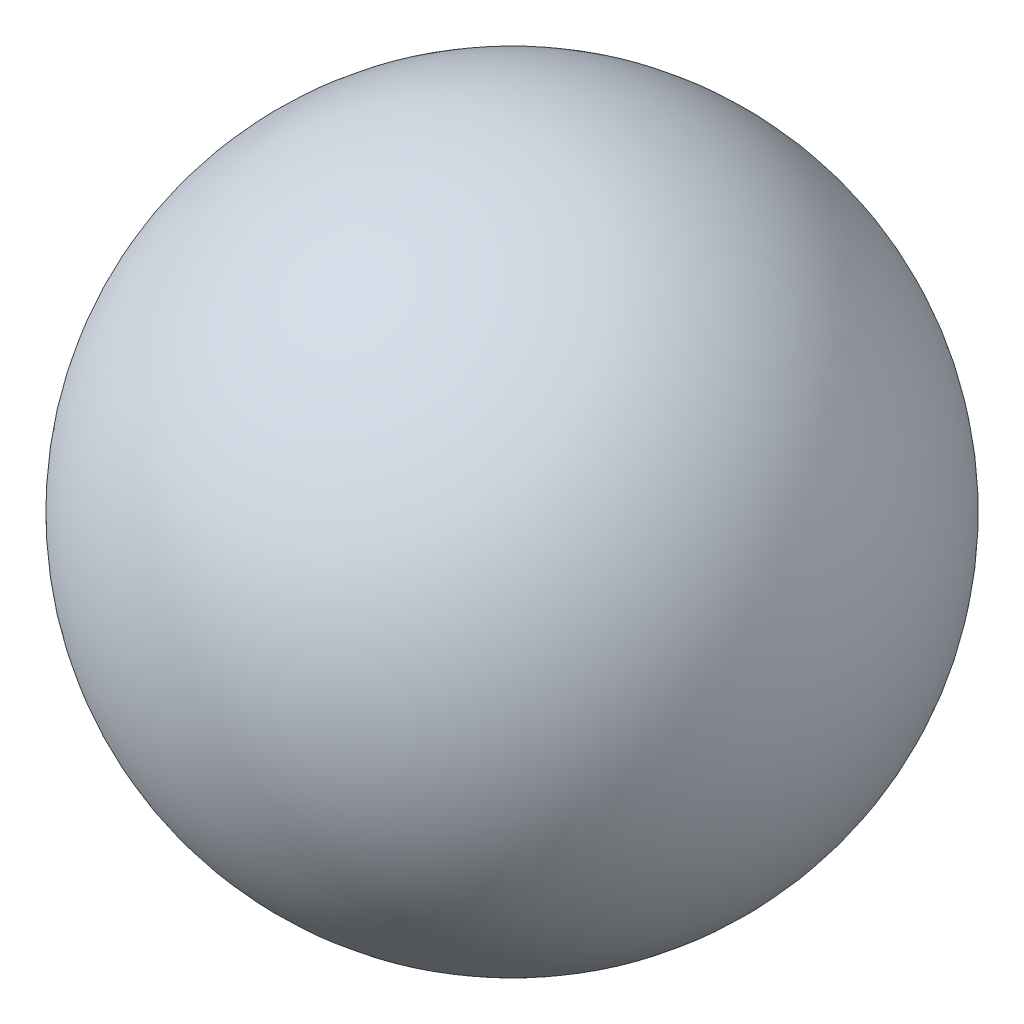
SolidWorks part; units mm, degrees
ref_plane "Front Plane" through (0, 0, 0) normal (0, 0, 1) x (1, 0, 0)
ref_plane "Top Plane" through (0, 0, 0) normal (0, 1, 0) x (1, 0, 0)
ref_plane "Right Plane" through (0, 0, 0) normal (1, 0, 0) x (0, 0, -1)
sketch "Sketch1" plane through (0, 0, 0) normal (0, 0, 1) x (1, 0, 0)
  line L1 (-50.5537, 931.9169) -> (50.5537, 931.9169) construction
  line L2 (0, 951.4169) -> (0, 943.4169)
  arc A0 (0, 943.4169) -> (0, 951.4169) centre (0, 947.4169) ccw
  point P4 (0, 931.9169)
  dimension "D1" = 8
  dimension "D2" = 31
revolve "Revolve1" add sketch "Sketch1" angle 360 about L2
equation "\"d_ext_rouleau\"= 90"
equation "\"epaisseur_rouleau\"=80"
equation "\"alesage-rouleau\"= 52"
equation "\"jeu_dent_rouleau\"= 2"
equation "\"profondeur_dent_rouleau\"=4"
equation "\"n_dent_roueau\"= 15"
equation "\"d_ext_roulement_rouleau\"= 42"
equation "\"d_int_roulement_rouleau\"= 20"
equation "\"B_roulement_rouleau\"= 12"
equation "\"r_roulement_rouleau\"= 0.6"
equation "\"d_bille_roulement_rouleau\"= 8"
equation "\"F_anneau_alesage_rouleau\"=1.85"
equation "\"G_anneau_alesage_rouleau\"=47.5"
equation "\"K_anneau_alesage_rouleau\"=3.75"
equation "\"d_vis_flasque_rouleau\"=5"
equation "\"l-x_vis_flasque_rouleau\"=4"
equation "\"g_anneau_arbre_rouleau\"=19"
equation "\"f_anneau_arbre_rouleau\"=1.3"
equation "\"k_anneau_arbre_rouleau\"=1.5"
equation "\"h_matrice\"= 18"
equation "\"d_matrice\"= 220"
equation "\"d_granulat\"= 8"
equation "\"zone_vide_matrice\" = 48"
equation "\"d_alesage_matrice\"=20"
equation "\"a_clavette_alesage_matrice\"=6"
equation "\"entrax_vis_rouleau\"=65"
equation "\"D1@Sketch1\"=\"d_bille_roulement_rouleau\""
equation "\"D2@Sketch1\"=\"d_int_roulement_rouleau\"+(\"d_ext_roulement_rouleau\"-\"d_int_roulement_rouleau\")/2"
